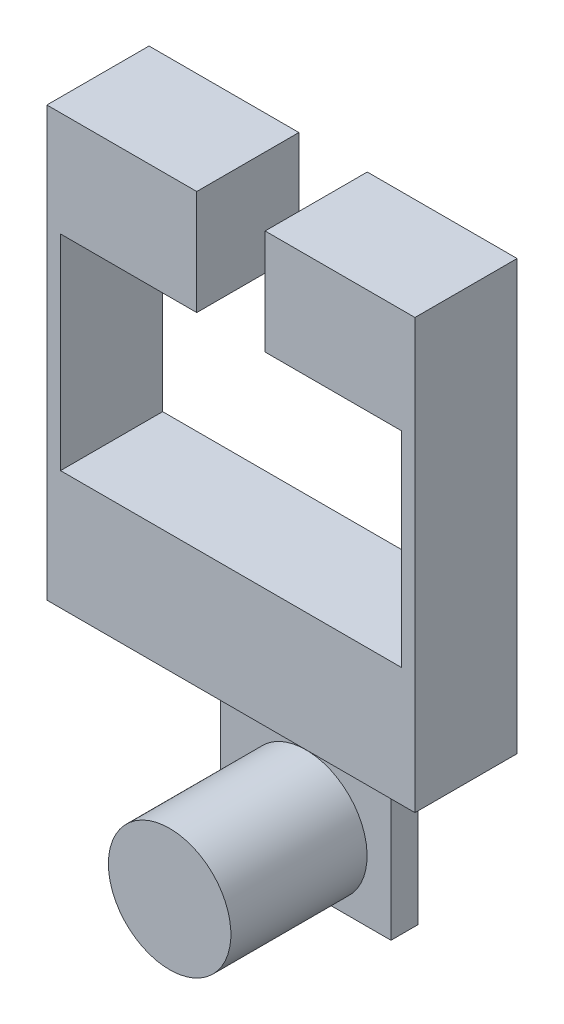
SolidWorks part; units mm, degrees
material "FEA Aluminum"
ref_plane "Front Plane" through (0, 0, 0) normal (0, 0, 1) x (1, 0, 0)
ref_plane "Top Plane" through (0, 0, 0) normal (0, 1, 0) x (1, 0, 0)
ref_plane "Right Plane" through (0, 0, 0) normal (1, 0, 0) x (0, 0, -1)
sketch "Sketch1" plane through (0, 0, 0) normal (0, 0, 1) x (1, 0, 0)
  line L1 (-34.3205, 79.975) -> (34.3205, 79.975)
  line L2 (-34.3205, 79.975) -> (-34.3205, 0)
  line L3 (-34.3205, 0) -> (34.3205, 0)
  line L4 (34.3205, 79.975) -> (34.3205, 0)
  dimension "D1" = 68.641
  dimension "D2" = 79.975
extrude "Main-Body" add sketch "Sketch1" along normal mid plane 19.05
sketch "Sketch2" plane through (0, 0, 9.525) normal (0, 0, 1) x (1, 0, 0)
  line L0 (0, 84.5954) -> (0, -7.8995) construction
  line L1 (-34.3205, 0) -> (34.3205, 0) construction
  line L2 (-31.7805, 60.417) -> (31.7805, 60.417)
  line L3 (-31.7805, 60.417) -> (-31.7805, 22.19)
  line L4 (-31.7805, 22.19) -> (31.7805, 22.19)
  line L5 (31.7805, 60.417) -> (31.7805, 22.19)
  dimension "D1" = 63.561
  dimension "D2" = 38.227
  dimension "D3" = 22.19
extrude "Lower-T-Cavity" cut sketch "Sketch2" against normal through all
sketch "Sketch3" plane through (0, 0, 9.525) normal (0, 0, 1) x (1, 0, 0)
  line L0 (0, 84.1431) -> (0, -5.638) construction
  line L1 (31.7805, 60.417) -> (-31.7805, 60.417) construction
  line L2 (-6.3754, 79.975) -> (6.3754, 79.975)
  line L3 (-6.3754, 79.975) -> (-6.3754, 60.417)
  line L4 (-6.3754, 60.417) -> (6.3754, 60.417)
  line L5 (6.3754, 79.975) -> (6.3754, 60.417)
  line L6 (34.3205, 79.975) -> (-34.3205, 79.975) construction
  dimension "D1" = 12.7508
extrude "Top-Slot" cut sketch "Sketch3" against normal through all
sketch "Sketch4" plane through (0, 0, -9.525) normal (0, 0, -1) x (-1, 0, 0)
  line L0 (0, 84.5954) -> (0, -5.9773) construction
  line L1 (34.3205, 0) -> (-34.3205, 0) construction
  line L2 (-15.875, 0) -> (15.875, 0)
  line L3 (-15.875, 0) -> (-15.875, -36.8236)
  line L4 (-15.875, -36.8236) -> (15.875, -36.8236)
  line L5 (15.875, 0) -> (15.875, -36.8236)
  dimension "D1" = 31.75
  dimension "D2" = 36.8236
extrude "Hanger" add sketch "Sketch4" against normal blind 5.08
sketch "Sketch5" plane through (0, 0, -9.525) normal (0, 0, -1) x (-1, 0, 0)
  circle A0 centre (0, -25.4) radius 11.4236
  dimension "D2" = 22.8473
  dimension "D1" = 25.4
extrude "Strap-Pin" add sketch "Sketch5" against normal blind 30.48
equation "\"Bracket_depth\"= 0.750in"
equation "\"Pin_diameter\"= 0.8995in"
equation "\"Pin_free_length\"= 1.000in"
equation "\"Hanger_width\"= 0.750in"
equation "\"Hanger_thickness\"= 0.2000in"
equation "\"Hanger_length\"= 1.000in"
equation "\"Web_thickness\"= 0.100in"
equation "\"Lip_height\"= 0.770in"
equation "\"Top_slot_width\"= 0.5020in"
equation "\"T_cavity_width\"= 2.5024in"
equation "\"T_cavity_height\"= 1.5050in"
equation "\"Crossmember_height\"= ( 3 * 1400 * 2.6024 / ( 2 * 0.75 * 10000 ) ) ^ ( 1 / 2 ) * 1in + 0.020in"
equation "\"D1@Sketch1\"=\"T_cavity_width\"+2*\"Web_thickness\""
equation "\"D2@Sketch1\"=\"Crossmember_height\"+\"T_cavity_height\"+\"Lip_height\""
equation "\"D1@Main-Body\" = \"Bracket_depth\""
equation "\"D1@Sketch2\"=\"T_cavity_width\""
equation "\"D2@Sketch2\"=\"T_cavity_height\""
equation "\"D3@Sketch2\"=\"Crossmember_height\""
equation "\"D1@Sketch3\"=\"Top_slot_width\""
equation "\"D2@Sketch4\"=\"Hanger_length\"+\"Pin_diameter\"/2"
equation "\"D1@Hanger\" = \"Hanger_thickness\""
equation "\"D1@Sketch5\"=\"Hanger_length\""
equation "\"D2@Sketch5\"=\"Pin_diameter\""
equation "\"D1@Strap-Pin\" = \"Pin_free_length\" + \"Hanger_thickness\""
